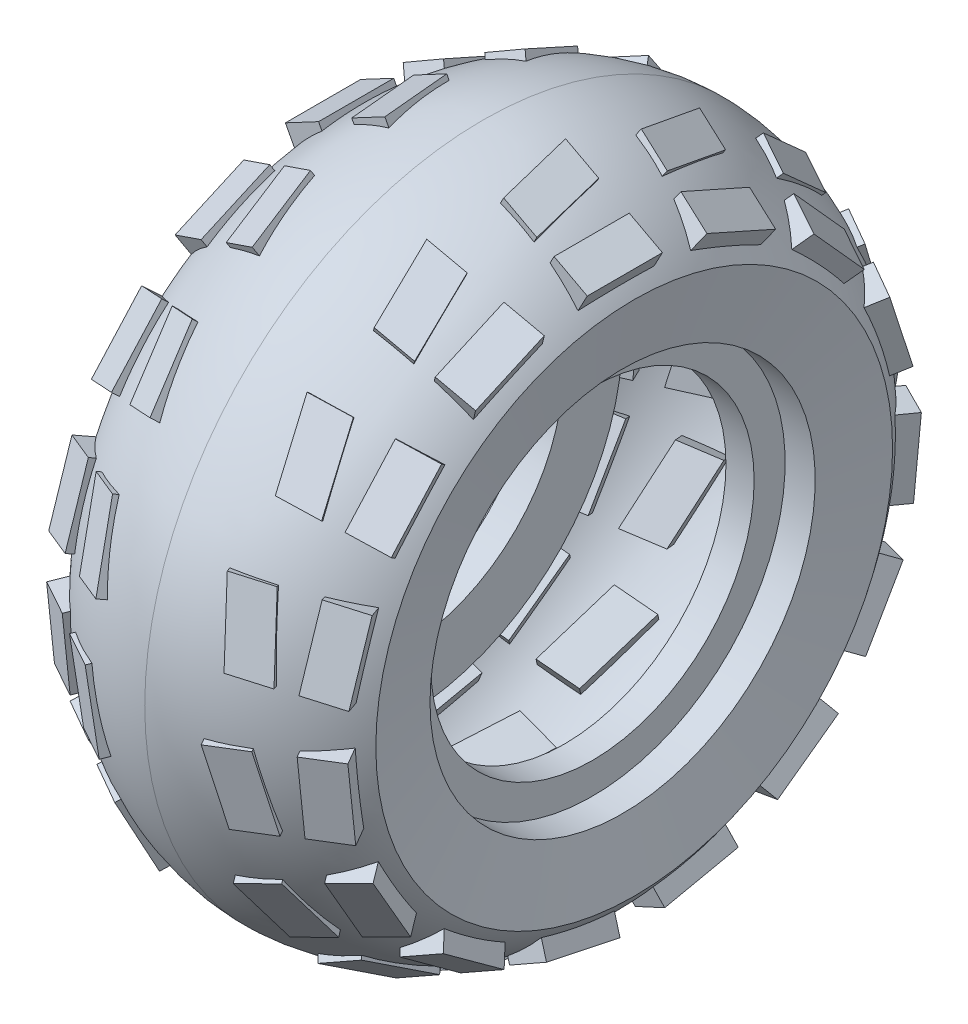
SolidWorks part; units mm, degrees
ref_plane "Front Plane" through (0, 0, 0) normal (0, 0, 1) x (1, 0, 0)
ref_plane "Top Plane" through (0, 0, 0) normal (0, 1, 0) x (1, 0, 0)
ref_plane "Right Plane" through (0, 0, 0) normal (1, 0, 0) x (0, 0, -1)
sketch "Sketch1" plane through (0, 0, 0) normal (0, 0, 1) x (1, 0, 0)
  line L0 (0, 0) -> (11.66, 0) construction
  line L1 (0, 8.6) -> (0, 10.25)
  line L2 (0, 10.25) -> (-1.6, 10.25)
  line L3 (-1.6, 10.25) -> (-2.2171, 13.75)
  line L4 (0, 8.6) -> (1.5, 8.6)
  line L5 (1.5, 8.6) -> (1.5, 11.75)
  line L6 (1.5, 11.75) -> (-0.3414, 11.75)
  line L7 (-0.3414, 11.75) -> (-0.5177, 12.75)
  line L8 (5.83, 0) -> (5.83, 22.562) construction
  line L9 (12.0014, 11.75) -> (12.1777, 12.75)
  line L10 (10.16, 11.75) -> (12.0014, 11.75)
  line L11 (10.16, 8.6) -> (10.16, 11.75)
  line L12 (11.66, 8.6) -> (10.16, 8.6)
  line L13 (13.26, 10.25) -> (13.8771, 13.75)
  line L14 (11.66, 10.25) -> (13.26, 10.25)
  line L15 (11.66, 8.6) -> (11.66, 10.25)
  arc A0 (-2.2171, 13.75) -> (5.83, 18) centre (5.965, 8.0009) cw
  arc A1 (-0.5177, 12.75) -> (5.83, 16.5) centre (5.6829, 9.5015) cw
  arc A2 (12.1777, 12.75) -> (5.83, 16.5) centre (5.9771, 9.5015) ccw
  arc A3 (13.8771, 13.75) -> (5.83, 18) centre (5.695, 8.0009) ccw
  dimension "D10" = 1.5
  dimension "D13" = 10
  dimension "D14" = 7
  dimension "D1" = 8.6
  dimension "D2" = 1.5
  dimension "D3" = 1.6
  dimension "D4" = 10.25
  dimension "D5" = 3.5
  dimension "D6" = 1.5
  dimension "D7" = 100
  dimension "D8" = 1
  dimension "D9" = 1.5
  dimension "D11" = 18
  dimension "D12" = 5.83
revolve "Revolve1" add sketch "Sketch1" angle 360 about L0
ref_plane "Plane1" through (0, 20, 0) normal (0, 1, 0) x (1, 0, 0)
ref_plane "Plane2" through (0, 16, 0) normal (0, 1, 0) x (1, 0, 0)
sketch "Sketch2" plane through (0, 16, 0) normal (0, 1, 0) x (1, 0, 0)
  line L0 (5.83, 18) -> (5.83, -18) construction
  line L1 (-2.2171, 0) -> (13.8771, 0) construction
  line L2 (-2.2171, -13.75) -> (-2.2171, 13.75) construction
  line L3 (13.8771, -13.75) -> (13.8771, 13.75) construction
ref_plane "Plane3" through (7.9173, 14.8902, 0) normal (0.4695, 0.8829, 0) x (0, 0, 1)
sketch "Sketch3" plane through (7.9173, 14.8902, 0) normal (0.4695, 0.8829, 0) x (0, 0, 1)
  line L0 (0, 35.0198) -> (0, -0.3093) construction
  line L2 (-1.5285, 5.1245) -> (2.4715, 5.1245)
  line L3 (-1.5285, 5.1245) -> (-1.5285, 3.1245)
  line L4 (-1.5285, 3.1245) -> (2.4715, 3.1245)
  line L5 (2.4715, 5.1245) -> (2.4715, 3.1245)
  dimension "D1" = 4
  dimension "D2" = 2
extrude "Boss-Extrude5" add sketch "Sketch3" along normal blind 3
pattern_circular "CirPattern2" count 15 over 360 about axis through (0, 0, 0) along (1, 0, 0) of "Boss-Extrude5"
sketch "Sketch6" plane through (7.9173, 14.8902, 0) normal (0.4695, 0.8829, 0) x (0, 0, 1)
  line L1 (-0.2225, 4.383) -> (-0.2225, -2.4394)
  dimension "D1" = 6.8224
ref_plane "Plane4" through (-5.3473, 10.0569, 0) normal (0.4695, -0.8829, 0) x (0, 0, 1)
sketch "Sketch7" plane through (-5.3473, 10.0569, 0) normal (0.4695, -0.8829, 0) x (0, 0, 1)
  line L0 (-18, -12.6591) -> (18, -12.6591) construction
  line L1 (2.3112, -4.9091) -> (-1.6888, -4.9091)
  line L2 (2.3112, -4.9091) -> (2.3112, -6.9091)
  line L3 (2.3112, -6.9091) -> (-1.6888, -6.9091)
  line L4 (-1.6888, -4.9091) -> (-1.6888, -6.9091)
  dimension "D1" = 4
  dimension "D2" = 2
  dimension "D3" = 5.75
extrude "Boss-Extrude6" add sketch "Sketch7" against normal blind 2.9
pattern_circular "CirPattern3" count 15 over 360 about axis through (0, 0, 0) along (1, 0, 0) of "Boss-Extrude6"
sketch "Sketch8" plane through (-5.3473, 10.0569, 0) normal (0.4695, -0.8829, 0) x (0, 0, 1)
  line L0 (2.3112, -10.9591) -> (-1.6888, -10.1591)
  line L1 (-1.6888, -10.1591) -> (-1.6888, -8.1591)
  line L2 (-1.6888, -8.1591) -> (2.3112, -8.9591)
  line L3 (2.3112, -8.9591) -> (2.3112, -10.9591)
  line L4 (-1.6888, -4.9091) -> (-1.6888, -6.9091) construction
  line L5 (-18, -12.6591) -> (18, -12.6591) construction
  dimension "D1" = 2
  dimension "D2" = 4
  dimension "D3" = 2.5
  dimension "D4" = 1.7
extrude "Boss-Extrude8" add sketch "Sketch8" against normal blind 3
pattern_circular "CirPattern4" count 15 over 360 about axis through (0, 0, 0) along (1, 0, 0) of "Boss-Extrude8"
sketch "Sketch9" plane through (7.9173, 14.8902, 0) normal (0.4695, 0.8829, 0) x (0, 0, 1)
  line L0 (2.5143, 2.136) -> (-1.4857, 1.336)
  line L1 (-1.4857, 1.336) -> (-1.4857, -0.664)
  line L2 (-1.4857, -0.664) -> (2.5143, 0.136)
  line L3 (2.5143, 0.136) -> (2.5143, 2.136)
  line L4 (-18, -2.364) -> (18, -2.364) construction
  dimension "D1" = 2
  dimension "D2" = 4
  dimension "D3" = 2.5
  dimension "D4" = 1.7
extrude "Boss-Extrude9" add sketch "Sketch9" along normal blind 3
pattern_circular "CirPattern5" count 15 over 360 about axis through (0, 0, 0) along (1, 0, 0) of "Boss-Extrude9"
